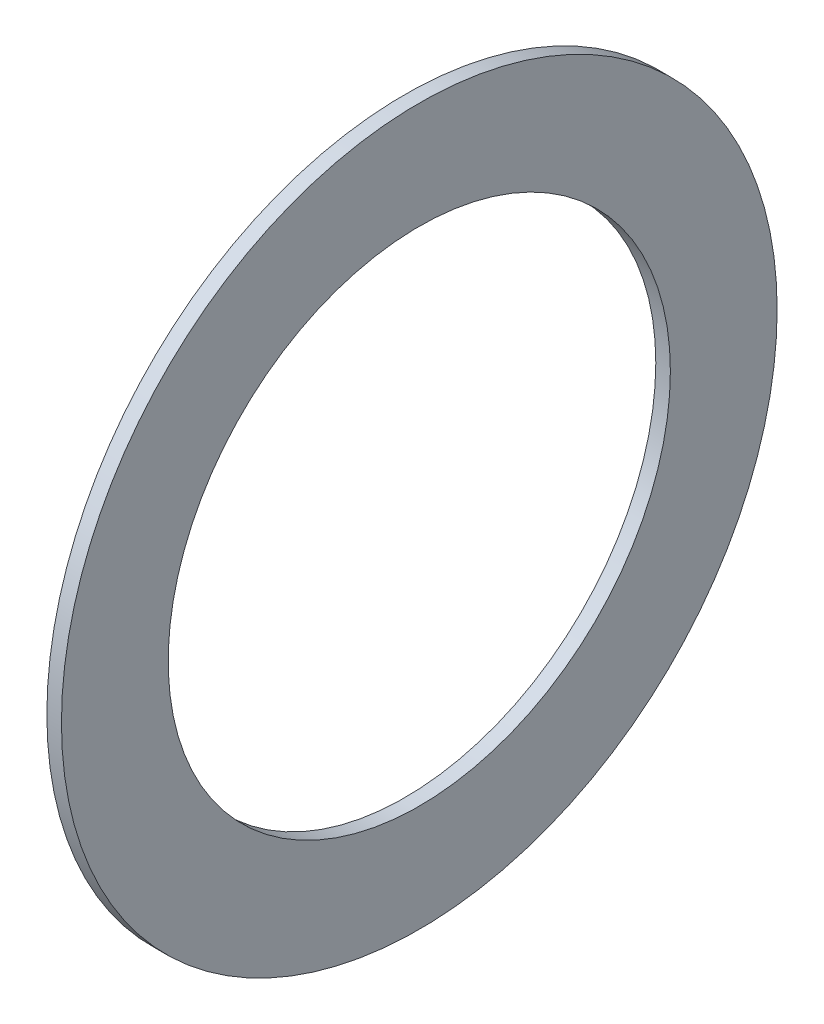
SolidWorks part; units mm, degrees
material "Teck"
ref_plane "Plan de face" through (0, 0, 0) normal (0, 0, 1) x (1, 0, 0)
ref_plane "Plan de dessus" through (0, 0, 0) normal (0, 1, 0) x (1, 0, 0)
ref_plane "Plan de droite" through (0, 0, 0) normal (1, 0, 0) x (0, 0, -1)
sketch "Esquisse1" plane through (0, 0, 0) normal (1, 0, 0) x (0, 0, -1)
  circle A0 centre (0, 0) radius 51.649
  circle A1 centre (0, 0) radius 73.6092
  circle A2 centre (0, 0) radius 51.649 construction
  circle A3 centre (0, 0) radius 73.6092 construction
extrude "Boss.-Extru.1" add sketch "Esquisse1" along normal blind 3
